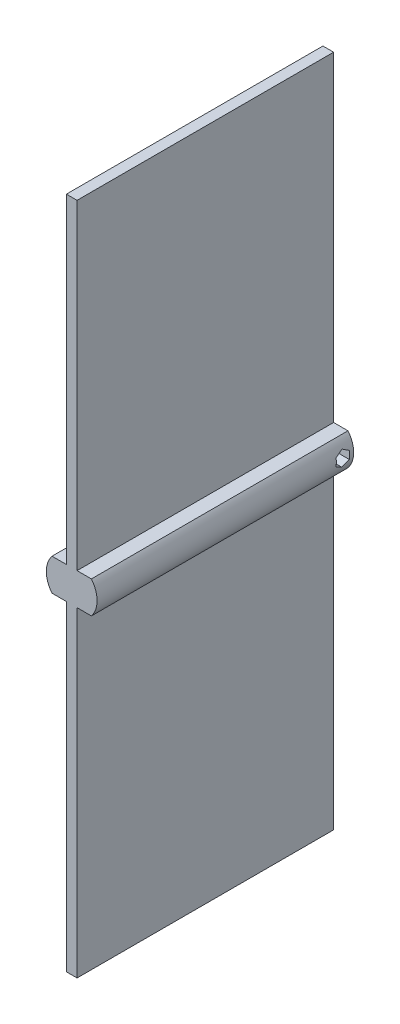
SolidWorks part; units mm, degrees
ref_plane "Front Plane" through (0, 0, 0) normal (0, 0, 1) x (1, 0, 0)
ref_plane "Top Plane" through (0, 0, 0) normal (0, 1, 0) x (1, 0, 0)
ref_plane "Right Plane" through (0, 0, 0) normal (1, 0, 0) x (0, 0, -1)
sketch "Sketch1" plane through (0, 0, 0) normal (0, 0, 1) x (1, 0, 0)
  circle A0 centre (0, 0) radius 4.75
  dimension "D1" = 9.5
extrude "Boss-Extrude1" add sketch "Sketch1" along normal blind 48
sketch "Sketch2" plane through (0, 0, 0) normal (0, 0, -1) x (-1, 0, 0)
  line L0 (1.8, 0) -> (-0.94, 0) construction
  line L1 (-0.94, 1.5351) -> (-0.94, -1.5351)
  arc A0 (-0.94, -1.5351) -> (-0.94, 1.5351) centre (0, 0) ccw
  point P7 (-0.94, 0)
  dimension "D1" = 3.6
  dimension "D2" = 2.74
extrude "Cut-Extrude1" cut sketch "Sketch2" against normal blind 10
sketch "Sketch3" plane through (0.94, 0, 0) normal (-1, 0, 0) x (0, 0, 1)
  line L0 (0, 1.5351) -> (0, -1.5351) construction
  line L1 (3.2307, 0.7541) -> (1.9623, 1.4429)
  line L2 (1.9623, 1.4429) -> (0.7316, 0.6888)
  line L3 (0.7316, 0.6888) -> (0.7693, -0.7541)
  line L4 (0.7693, -0.7541) -> (2.0377, -1.4429)
  line L5 (2.0377, -1.4429) -> (3.2684, -0.6888)
  line L6 (3.2684, -0.6888) -> (3.2307, 0.7541)
  line L8 (0, 0) -> (2, 0) construction
  circle A1 centre (2, 0) radius 1.25 construction
  dimension "D1" = 2.5
  dimension "D2" = 2
  dimension "D3" = 1.4429
extrude "Cut-Extrude2" cut sketch "Sketch3" against normal through all
sketch "Sketch4" plane through (0, 0, 0) normal (0, 0, -1) x (-1, 0, 0)
  line L0 (-3.6827, 3) -> (3.6827, 3)
  line L1 (-3.6827, -3) -> (3.6827, -3)
  circle A0 centre (0, 0) radius 4.75 construction
  arc A1 (-3.6827, -3) -> (3.6827, -3) centre (0, 0) ccw
  arc A2 (3.6827, 3) -> (-3.6827, 3) centre (0, 0) ccw
  dimension "D1" = 3
  dimension "D2" = 3
extrude "Cut-Extrude3" cut sketch "Sketch4" against normal up to next
sketch "Sketch5" plane through (0, 3, 0) normal (0, 1, 0) x (1, 0, 0)
  line L0 (0, 0) -> (0, -48) construction
  line L1 (3.6827, -48) -> (-3.6827, -48) construction
  line L2 (3.6827, 0) -> (-3.6827, 0) construction
  line L3 (-1, -48) -> (1, -48)
  line L4 (-1, -48) -> (-1, 0)
  line L5 (-1, 0) -> (1, 0)
  line L6 (1, -48) -> (1, 0)
  line L7 (-1, -48) -> (1, 0) construction
  line L8 (-1, 0) -> (1, -48) construction
  point P5 (0, -24)
  dimension "D1" = 2
extrude "Boss-Extrude2" add sketch "Sketch5" along normal blind 60
mirror "Mirror2" about plane through (0, 0, 0) normal (0, 1, 0) of "Boss-Extrude2"
